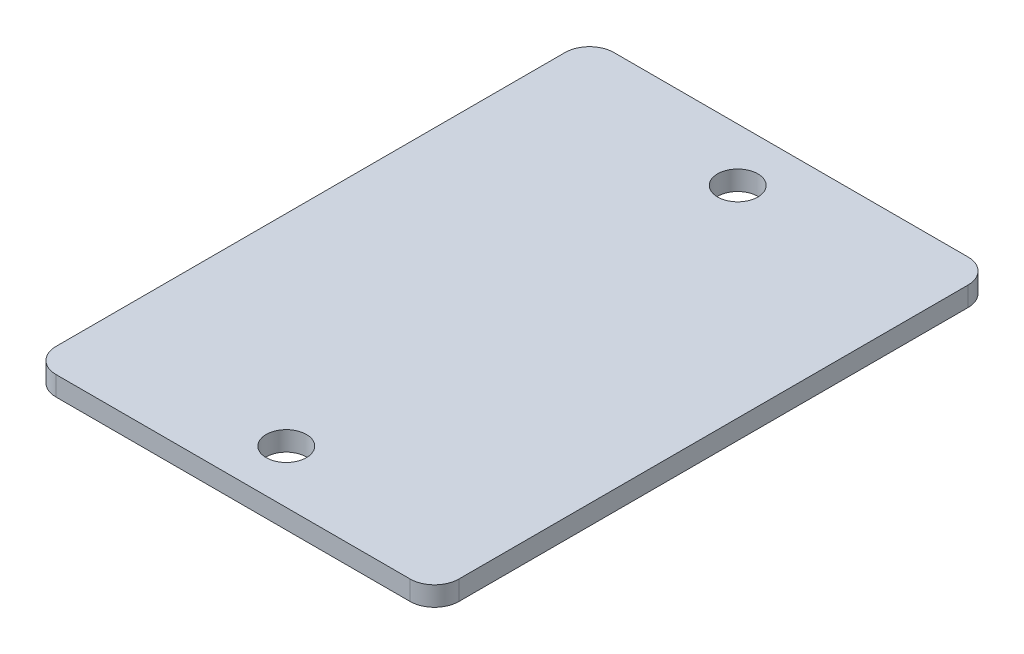
SolidWorks part; units mm, degrees
ref_plane "Front Plane" through (0, 0, 0) normal (0, 0, 1) x (1, 0, 0)
ref_plane "Top Plane" through (0, 0, 0) normal (0, 1, 0) x (1, 0, 0)
ref_plane "Right Plane" through (0, 0, 0) normal (1, 0, 0) x (0, 0, -1)
sketch "Sketch1" plane through (0, 0, 0) normal (0, 1, 0) x (1, 0, 0)
  line L0 (-375.6911, 0) -> (18408.8634, 0) construction
  line L1 (0, -375.6911) -> (0, 18408.8634) construction
  line L3 (-16.51, 22.86) -> (16.51, 22.86)
  line L4 (-16.51, 22.86) -> (-16.51, -22.86)
  line L5 (-16.51, -22.86) -> (16.51, -22.86)
  line L6 (16.51, 22.86) -> (16.51, -22.86)
  line L7 (-16.51, 22.86) -> (16.51, -22.86) construction
  line L8 (-16.51, -22.86) -> (16.51, 22.86) construction
  circle A0 centre (0, 18.5) radius 1.65
  circle A1 centre (0, -18.5) radius 1.65
  point P4 (0, 0)
  point P14 (0, 17.4039)
  point P15 (0, 0)
  dimension "D4" = 3.3
  dimension "D1" = 33.02
  dimension "D2" = 45.72
  dimension "D3" = 37
extrude "Boss-Extrude1" add sketch "Sketch1" along normal blind 1.6
fillet "Fillet1" radius 2 4 edges at (-16.51, 0.8, 22.86) (16.51, 0.8, 22.86) (16.51, 0.8, -22.86) (-16.51, 0.8, -22.86)
equation "\"Frame_Size\" = 220"
equation "\"Frame_Thickness\" = 6"
equation "\"Arm_Width\" = 30"
equation "\"Motor_Mount_Hole_Diameter\" = 8"
equation "\"Motor_Shaft_Diameter\" = 3"
equation "\"Screw_Nut_Diameter\" = 5"
equation "\"Screw_Diameter\" = 3"
equation "\"Screw_Shaft_Length\" = 10"
equation "\"Screw_Hole_Separation_C2C\" = 20"
equation "\"Solder_Board_Small_Screw_Hole_Separation\" = 37"
equation "\"Solder_Board_Small_Length\" = 45.72"
equation "\"Solder_Board_Small_Width\" = 33.02"
equation "\"Solder_Board_Small_Thickness\" = 1.6"
equation "\"D1@Sketch1\"=\"Solder_Board_Small_Width\""
equation "\"D2@Sketch1\"=\"Solder_Board_Small_Length\""
equation "\"D3@Sketch1\"=\"Solder_Board_Small_Screw_Hole_Separation\""
equation "\"Solder_Board_Small_Screw_Hole_Diameter\" = 3.3"
equation "\"D4@Sketch1\"=\"Solder_Board_Small_Screw_Hole_Diameter\""
equation "\"D1@Boss-Extrude1\"=\"Solder_Board_Small_Thickness\""
